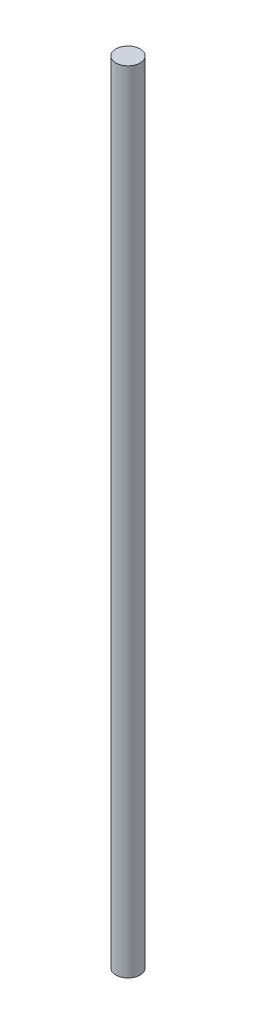
SolidWorks part; units mm, degrees
material "Acero inoxidable al cromo"
ref_plane "Alzado" through (0, 0, 0) normal (0, 0, 1) x (1, 0, 0)
ref_plane "Planta" through (0, 0, 0) normal (0, 1, 0) x (1, 0, 0)
ref_plane "Vista lateral" through (0, 0, 0) normal (1, 0, 0) x (0, 0, -1)
sketch "Croquis1" plane through (0, 0, 0) normal (0, 1, 0) x (1, 0, 0)
  circle A0 centre (0, 0) radius 10
extrude "Saliente-Extruir1" add sketch "Croquis1" along normal mid plane 650
